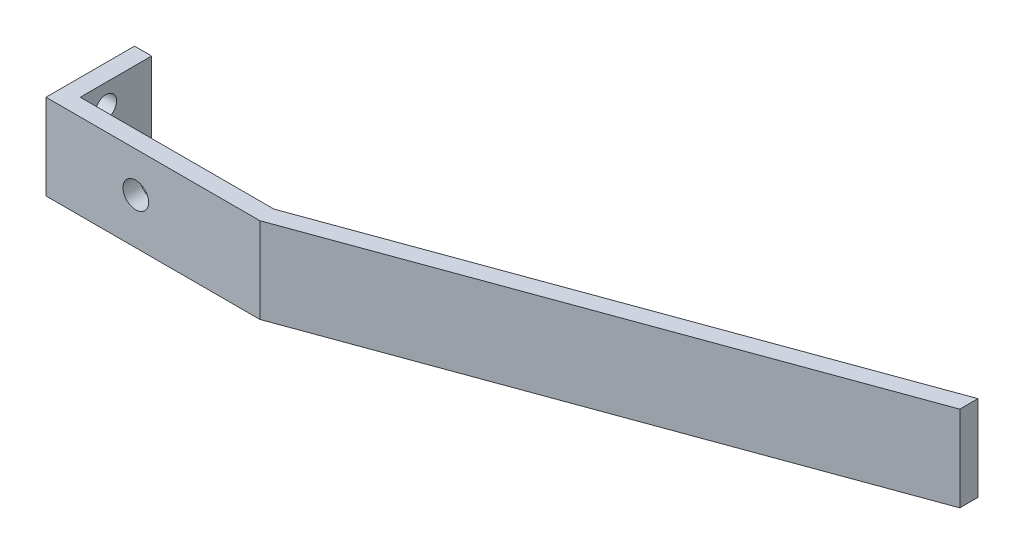
SolidWorks part; units mm, degrees
ref_plane "Спереди" through (0, 0, 0) normal (0, 0, 1) x (1, 0, 0)
ref_plane "Сверху" through (0, 0, 0) normal (0, 1, 0) x (1, 0, 0)
ref_plane "Справа" through (0, 0, 0) normal (1, 0, 0) x (0, 0, -1)
sketch "Эскиз1" plane through (0, 0, 0) normal (0, 1, 0) x (1, 0, 0)
  line L0 (50, 0) -> (170, 43.6764)
  line L1 (0, 0) -> (50, 0)
  line L2 (0, 0) -> (0, 4)
  line L3 (4, 4) -> (49.2947, 4)
  line L4 (170, 47.9331) -> (170, 43.6764)
  line L5 (49.2947, 4) -> (170, 47.9331)
  line L6 (4, 4) -> (4, 20.7)
  line L7 (4, 20.7) -> (0, 20.7)
  line L8 (0, 4) -> (0, 20.7)
  dimension "D1" = 4
  dimension "D2" = 50
  dimension "D3" = 4
  dimension "D4" = 16.7
  dimension "D5" = 20
  dimension "D6" = 4
  dimension "D7" = 4
  dimension "D8" = 120
extrude "Бобышка-Вытянуть1" add sketch "Эскиз1" along normal blind 20
sketch "Эскиз2" plane through (0, 0, 0) normal (-1, 0, 0) x (0, 0, 1)
  line L0 (-10, 20) -> (-10, 0) construction
  line L1 (-20.7, 20) -> (0, 20) construction
  line L2 (-20.7, 0) -> (0, 0) construction
  line L3 (0, 20) -> (0, 0) construction
  circle A0 centre (-10, 5) radius 2.5
  circle A1 centre (-10, 15) radius 2.5
  dimension "D2" = 5
  dimension "D1" = 10
  dimension "D3" = 5
  dimension "D4" = 5
extrude "Вырез-Вытянуть1" cut sketch "Эскиз2" against normal blind 4
sketch "Эскиз3" plane through (0, 0, 0) normal (0, 0, 1) x (1, 0, 0)
  line L0 (0, 20) -> (0, 0) construction
  circle A0 centre (21, 10.6901) radius 3
  dimension "D1" = 6
  dimension "D2" = 21
extrude "Вырез-Вытянуть2" cut sketch "Эскиз3" against normal blind 4
